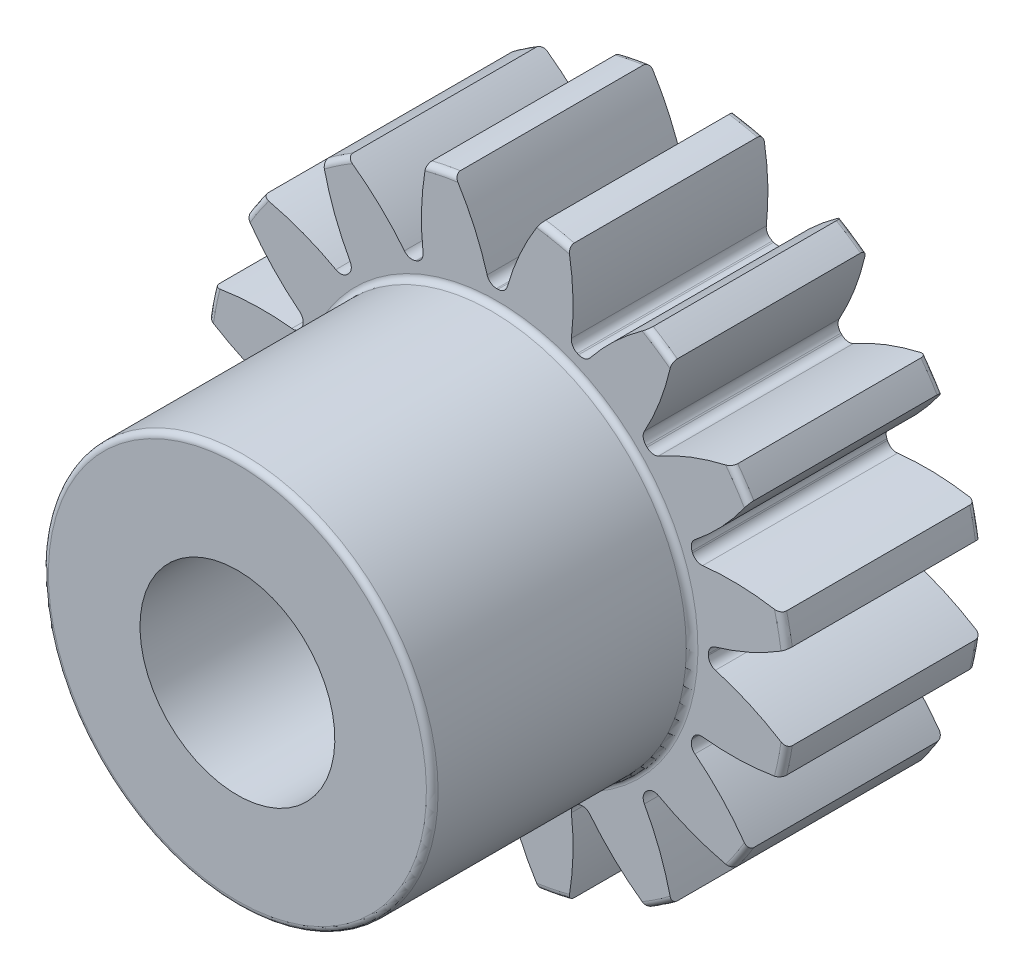
SolidWorks part; units mm, degrees
ref_plane "Front Plane" through (0, 0, 0) normal (0, 0, 1) x (1, 0, 0)
ref_plane "Top Plane" through (0, 0, 0) normal (0, 1, 0) x (1, 0, 0)
ref_plane "Right Plane" through (0, 0, 0) normal (1, 0, 0) x (0, 0, -1)
sketch "Sketch1" plane through (0, 0, 0) normal (0, 0, 1) x (1, 0, 0)
  line L0 (-203.2, 0) -> (203.2, 0) construction
  circle A0 centre (0, 0) radius 4.5 construction
  circle A1 centre (0, 0) radius 4 construction
  circle A2 centre (0, 0) radius 3.25 construction
  circle A3 centre (0, 0) radius 3 construction
  circle A4 centre (0, 0) radius 1.5 construction
  dimension "D2" = 0.5
  dimension "D3" = 1.25
  dimension "D1" = 1.25
sketch "Sketch2" plane through (0, 0, 0) normal (1, 0, 0) x (0, 0, -1)
  line L0 (0, 0) -> (-3, 0) construction
  line L1 (-3, 0) -> (-7, 0) construction
  dimension "Overall Width" = 7
  dimension "Face Width" = 3
sketch "Sketch4" plane through (0, 0, 0) normal (1, 0, 0) x (0, 0, -1)
  line L0 (-7, 1.5) -> (-7, 3)
  line L1 (-7, 3) -> (-3, 3)
  line L2 (-3, 3) -> (-3, 4.5)
  line L3 (-3, 4.5) -> (0, 4.5)
  line L4 (0, 4.5) -> (0, 1.5)
  line L5 (-3, 3) -> (-3, 0) construction
  line L6 (0, 4.5) -> (0, -4.5) construction
  line L7 (-3, 3) -> (0, 3) construction
  line L12 (-7, 1.5) -> (0, 1.5)
revolve "Revolve1" add sketch "Sketch4" angle 360 about L1
fillet "Fillet2" radius 0.09 4 edges at (0, 3, 7) (0, 3, 3) (0, 4.5, 3) (0, 4.5, 0)
sketch "Sketch7" plane through (0, 0, 3) normal (0, 0, 1) x (1, 0, 0)
  line L0 (0, 0) -> (0, 4.5) construction
  line L1 (0.3921, 3.9807) -> (0.6205, 4.457) construction
  line L3 (0.8779, 4.4135) -> (0.7804, 3.9231) construction
  line L4 (0.7804, 3.9231) -> (0.634, 3.1876) construction
  line L5 (0, 0) -> (0.634, 3.1876) construction
  line L6 (0.3921, 3.9807) -> (0, 0) construction
  line L7 (0.3921, 3.9807) -> (0.4411, 4.4783) construction
  line L8 (0.3921, 3.9807) -> (0, 0) construction
  circle A0 centre (0, 0) radius 4.5 construction
  arc A1 (-0.0104, 3.25) -> (0.0104, 3.25) centre (0, 0) cw
  circle A2 centre (0, 0) radius 3.25 construction
  arc A3 (-0.3921, 3.9807) -> (0.3921, 3.9807) centre (0, 0) cw construction
  circle A4 centre (0, 0) radius 4 construction
  arc A5 (1.0952, 4.3647) -> (0.6585, 4.4516) centre (0, 0) ccw construction
  arc A6 (0.3921, 3.9807) -> (1.1611, 3.8278) centre (0, 0) cw construction
  arc A7 (-0.6585, 4.4516) -> (0.6585, 4.4516) centre (0, 0) cw
  arc A8 (0.1551, 3.3585) -> (0.6585, 4.4516) centre (3.9986, 2.2508) cw
  arc A9 (-0.1551, 3.3585) -> (-0.6585, 4.4516) centre (-3.9986, 2.2508) ccw
  arc A10 (-0.0104, 3.25) -> (-0.1551, 3.3585) centre (-0.0109, 3.4) cw
  arc A11 (0.0104, 3.25) -> (0.1551, 3.3585) centre (0.0109, 3.4) ccw
  point P26 (-0.1248, 3.2476)
  point P29 (0.1248, 3.2476)
  dimension "D4" = 0.15
  dimension "D5" = 4
  dimension "D3" = 20
  dimension "D1" = 1.5708
  dimension "D2" = 0.7854
extrude "Cut-Extrude2" cut sketch "Sketch7" against normal through all
pattern_circular "CirPattern1" count 16 over 360 about axis through (0, 0, 0) along (0, 0, 1) of "Cut-Extrude2"
equation "\"D1@Sketch1\"=2.5*(\"Pitch Dia.@Sketch1\"/\"Number of Teeth@Sketch1\")"
equation "\"D1@CirPattern1\"=\"Number of Teeth@Sketch1\""
equation "\"D1@Fillet2\"=\"OD@Sketch1\"*.01"
equation "\"D1@Sketch7\"=3.14159*(\"Pitch Dia.@Sketch1\"/\"Number of Teeth@Sketch1\")"
equation "\"D2@Sketch7\"=\"D1@Sketch7\"/2"
equation "\"D4@Sketch7\"=\"D1@Sketch7\"*.0955"
equation "\"D5@Sketch7\"=\"Pitch Dia.@Sketch1\"/2"
